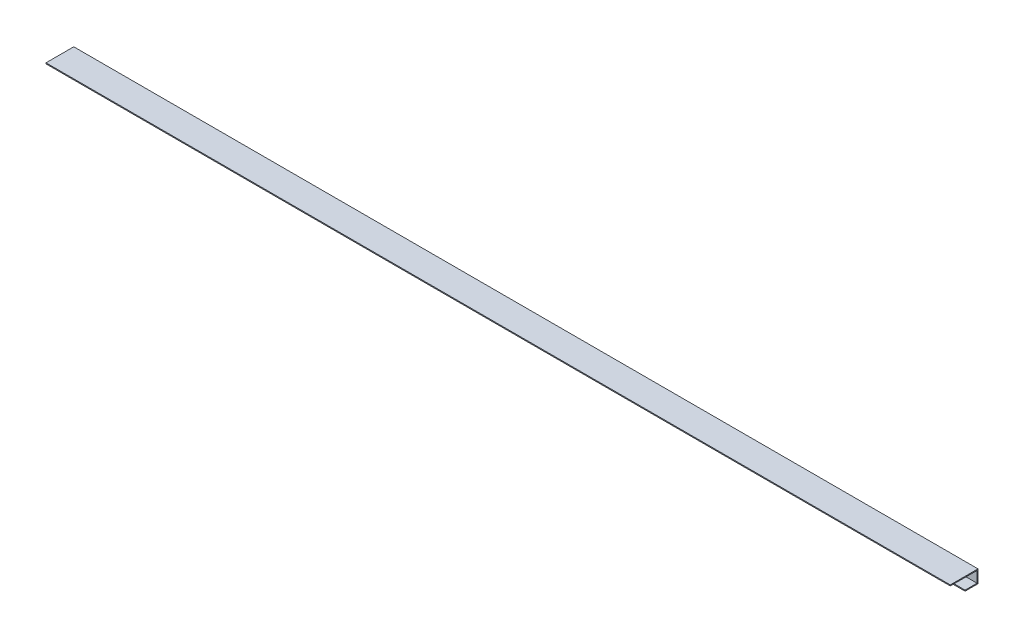
SolidWorks part; units mm, degrees
ref_plane "Front Plane" through (0, 0, 0) normal (0, 0, 1) x (1, 0, 0)
ref_plane "Top Plane" through (0, 0, 0) normal (0, 1, 0) x (1, 0, 0)
ref_plane "Right Plane" through (0, 0, 0) normal (1, 0, 0) x (0, 0, -1)
sketch "Sketch1" plane through (0, 0, 0) normal (1, 0, 0) x (0, 0, -1)
  line L0 (0, 0) -> (58, 0)
  line L1 (58, 0) -> (58, -27)
  line L2 (58, -27) -> (31, -27)
  line L3 (0, -2) -> (56, -2)
  line L4 (56, -2) -> (56, -25)
  line L5 (56, -25) -> (31, -25)
  line L6 (0, 0) -> (0, -2)
  line L7 (31, -25) -> (31, -27)
  dimension "D1" = 2
  dimension "D2" = 58
  dimension "D3" = 27
  dimension "D4" = 27
extrude "Boss-Extrude1" add sketch "Sketch1" along normal blind 1890
equation "\"door_base_short7_R1_L_open_Single_height\"=1890.0"
equation "\"D1@Boss-Extrude1\"= \"door_base_short7_L1_L_open_Single_height\""
equation "\"CarBeamWidth\"=700.0"
equation "\"WheelWidth\"=650.0"
equation "\"Wheel_FrontBoxDistance\"=1390.0"
equation "\"MetalSheet_3mm_length\"=5030.0"
equation "\"MetalSheet_3mm_width\"=1923.0"
equation "\"MetalSheet_3mm_FloorCut_L_length\"=1764.0"
equation "\"MetalSheet_3mm_FloorCut_L_disdance\"=1665.0"
equation "\"MetalSheet_3mm_FloorCut_R_length\"=1764.0"
equation "\"MetalSheet_3mm_FloorCut_R_disdance\"=1665.0"
equation "\"indoorHeight\"=1940.0"
equation "\"haveDoor_R\"=1"
equation "\"side_door_bottom_R_3mm_length\"=1934.0"
equation "\"1Bar_Side_RF_3mm_length\"=1493.0"
equation "\"1Bar_Side_RB_3mm_length\"=1493.0"
equation "\"DoorSeparator_RF_3mm_withHinge_toFrontDistance\"=1673.0"
equation "\"DoorSeparator_RF_3mm_withHinge_exist\"=1"
equation "\"DoorSeparator_RB_3mm_withHinge_toFrontDistance\"=3427.0"
equation "\"DoorSeparator_RB_3mm_withHinge_exist\"=1"
equation "\"Door_R1_L_open_Single_toFrontDistance\"=2547.5"
equation "\"Door_R1_L_open_Single_exist\"=1"
equation "\"door_base_long7_R1_L_open_Single_height\"=1890.0"
equation "\"door_base_short7_R1_L_open_Single_width\"=864"
equation "\"Door_R1_R_open_Single_toFrontDistance\"=3422.0"
equation "\"Door_R1_R_open_Single_exist\"=1"
equation "\"door_base_long7_R1_R_open_Single_height\"=1890.0"
equation "\"door_base_short7_R1_R_open_Single_height\"=1890.0"
equation "\"door_base_short7_R1_R_open_Single_width\"=864"
equation "\"x\"=66.0"
equation "\"da\"=62.0"
equation "\"SquareTube_length\"=1923.0"
equation "\"channelSteel_length\"=5030.0"
equation "\"SquareTube_inFront_AvgDistance\"=285.0"
equation "\"SquareTube_inFront_TotalCount\"=5"
equation "\"SquareTube_inFront1_cutDepth50_R\"=0.5"
equation "\"SquareTube_inFront1_cutDepth50_L\"=0.5"
equation "\"SquareTube_inFront2_cutDepth50_R\"=0.5"
equation "\"SquareTube_inFront2_cutDepth50_L\"=0.5"
equation "\"SquareTube_inFront3_cutDepth50_R\"=0.5"
equation "\"SquareTube_inFront3_cutDepth50_L\"=0.5"
equation "\"SquareTube_inFront4_cutDepth50_R\"=0.5"
equation "\"SquareTube_inFront4_cutDepth50_L\"=0.5"
equation "\"SquareTube_inFront5_cutDepth50_R\"=50"
equation "\"SquareTube_inFront5_cutDepth50_L\"=50"
equation "\"SquareTube_inFront6_cutDepth50_R\"=50"
equation "\"SquareTube_inFront6_cutDepth50_L\"=50"
equation "\"SquareTube_inFront7_cutDepth50_R\"=50"
equation "\"SquareTube_inFront7_cutDepth50_L\"=50"
equation "\"SquareTube_inFront8_cutDepth50_R\"=50"
equation "\"SquareTube_inFront8_cutDepth50_L\"=50"
equation "\"SquareTube_inFront9_cutDepth50_R\"=50"
equation "\"SquareTube_inFront9_cutDepth50_L\"=50"
equation "\"SquareTube_inFront10_cutDepth50_R\"=50"
equation "\"SquareTube_inFront10_cutDepth50_L\"=50"
equation "\"SquareTube_inFront11_cutDepth50_R\"=50"
equation "\"SquareTube_inFront11_cutDepth50_L\"=50"
equation "\"SquareTube_inFront12_cutDepth50_R\"=50"
equation "\"SquareTube_inFront12_cutDepth50_L\"=50"
equation "\"SquareTube_inFront13_cutDepth50_R\"=50"
equation "\"SquareTube_inFront13_cutDepth50_L\"=50"
equation "\"SquareTube_inFront14_cutDepth50_R\"=50"
equation "\"SquareTube_inFront14_cutDepth50_L\"=50"
equation "\"SquareTube_inBack_AvgDistance\"=333.125"
equation "\"SquareTube_inBack_TotalCount\"=9"
equation "\"SquareTube_inBack1_cutDepth50_R\"=50"
equation "\"SquareTube_inBack1_cutDepth50_L\"=50"
equation "\"SquareTube_inBack2_cutDepth50_R\"=50"
equation "\"SquareTube_inBack2_cutDepth50_L\"=50"
equation "\"SquareTube_inBack3_cutDepth50_R\"=50"
equation "\"SquareTube_inBack3_cutDepth50_L\"=50"
equation "\"SquareTube_inBack4_cutDepth50_R\"=50"
equation "\"SquareTube_inBack4_cutDepth50_L\"=50"
equation "\"SquareTube_inBack5_cutDepth50_R\"=50"
equation "\"SquareTube_inBack5_cutDepth50_L\"=50"
equation "\"SquareTube_inBack6_cutDepth50_R\"=0.5"
equation "\"SquareTube_inBack6_cutDepth50_L\"=0.5"
equation "\"SquareTube_inBack7_cutDepth50_R\"=0.5"
equation "\"SquareTube_inBack7_cutDepth50_L\"=0.5"
equation "\"SquareTube_inBack8_cutDepth50_R\"=0.5"
equation "\"SquareTube_inBack8_cutDepth50_L\"=0.5"
equation "\"boxLength\"=5100.0"
equation "\"boxWidth\"=1930.0"
equation "\"indoorHeight_para\"=25.0"
equation "\"rearLightHeight_para\"=265.0"
equation "\"doorColumnBar_A_FR_3mm_length_Cut\"=2310.0"
equation "\"A\"=0.0"
equation "\"side_door_bottom_R_3mm_toFrontDistance\"=1583.0"
equation "\"door_base_double_BL_height\"=1890.0"
equation "\"door_base_short7_BL_Single_height\"=1890.0"
equation "\"door_base_short7_BL_Single_width\"=864"
equation "\"door_base_long7_BR_Single_height\"=1890.0"
equation "\"door_base_short7_BR_Single_height\"=1890.0"
equation "\"door_base_short7_BR_Single_width\"=864"
equation "\"doorColumnBar_A_FL_3mm_length_Cut\"=2310.0"
equation "\"B\"=0.0"
equation "\"haveDoor_L\"=1"
equation "\"side_door_bottom_L_3mm_length\"=1934.0"
equation "\"side_door_bottom_L_3mm_toFrontDistance\"=1583.0"
equation "\"1Bar_Side_LF_3mm_length\"=1493.0"
equation "\"1Bar_Side_LB_3mm_length\"=1493.0"
equation "\"DoorSeparator_LF_3mm_withHinge_toFrontDistance\"=1673.0"
equation "\"DoorSeparator_LF_3mm_withHinge_exist\"=1"
equation "\"DoorSeparator_LB_3mm_withHinge_toFrontDistance\"=3427.0"
equation "\"DoorSeparator_LB_3mm_withHinge_exist\"=1"
equation "\"Door_L1_L_open_Single_toFrontDistance\"=3422.0"
equation "\"Door_L1_L_open_Single_exist\"=1"
equation "\"door_base_long7_L1_L_open_Single_height\"=1890.0"
equation "\"door_base_short7_L1_L_open_Single_height\"=1890.0"
equation "\"door_base_short7_L1_L_open_Single_width\"=864"
equation "\"Door_L1_R_open_Single_toFrontDistance\"=2547.5"
equation "\"Door_L1_R_open_Single_exist\"=1"
equation "\"door_base_long7_L1_R_open_Single_height\"=1890.0"
equation "\"door_base_short7_L1_R_open_Single_height\"=1890.0"
equation "\"door_base_short7_L1_R_open_Single_width\"=864"
